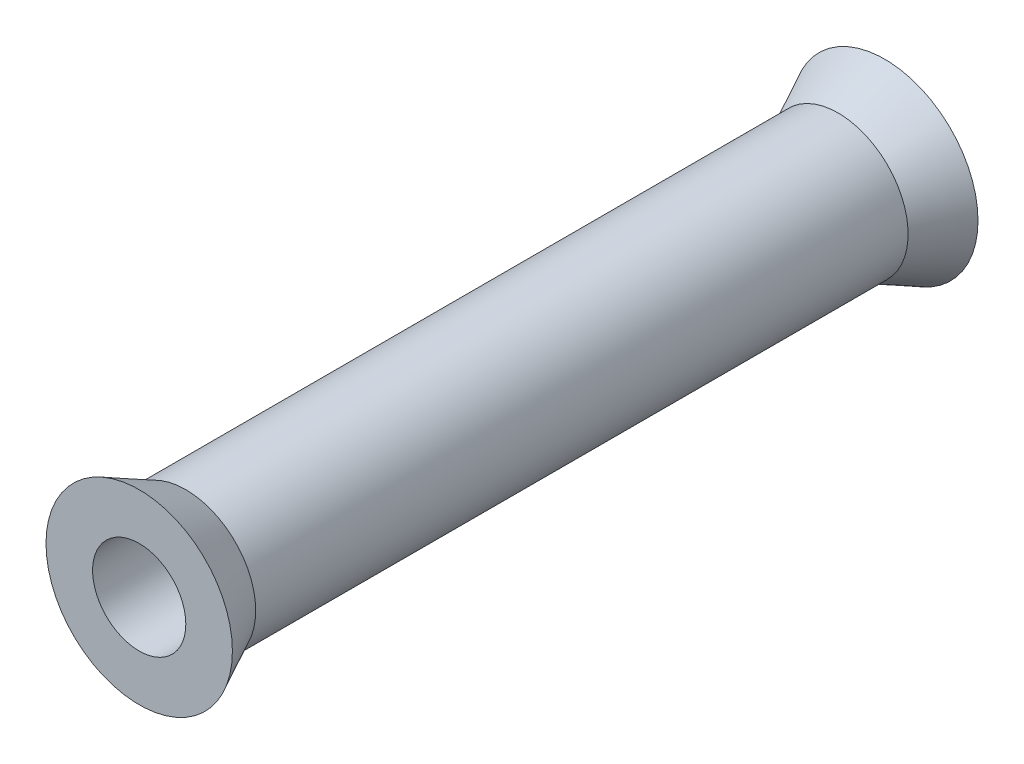
SolidWorks part; units mm, degrees
material "6061-T6 (SS)"
ref_plane "Front Plane" through (0, 0, 0) normal (0, 0, 1) x (1, 0, 0)
ref_plane "Top Plane" through (0, 0, 0) normal (0, 1, 0) x (1, 0, 0)
ref_plane "Right Plane" through (0, 0, 0) normal (1, 0, 0) x (0, 0, -1)
sketch "Sketch1" plane through (0, 0, 0) normal (0, 0, 1) x (1, 0, 0)
  circle A0 centre (0, 0) radius 6.35
  circle A1 centre (0, 0) radius 3.175
  dimension "D1" = 12.7
  dimension "D2" = 6.35
extrude "Boss-Extrude1" add sketch "Sketch1" along normal mid plane 50.8
sketch "Sketch2" plane through (0, 0, 0) normal (1, 0, 0) x (0, 0, -1)
  line L0 (0, 0) -> (0, 7.9375) construction
  line L1 (-28.575, 7.9375) -> (-22.225, 4.7625)
  line L2 (28.575, 11.1125) -> (-28.575, 11.1125)
  line L3 (28.575, 11.1125) -> (28.575, 4.7625)
  line L4 (28.575, 4.7625) -> (-28.575, 4.7625)
  line L5 (-28.575, 11.1125) -> (-28.575, 4.7625)
  line L6 (28.575, 11.1125) -> (-28.575, 4.7625) construction
  line L7 (28.575, 4.7625) -> (-28.575, 11.1125) construction
  line L8 (22.225, 4.7625) -> (28.575, 7.9375)
  line L9 (0, 0) -> (-13.5475, 0) construction
  dimension "D1" = 6.35
  dimension "D2" = 6.35
  dimension "D3" = 7.9375
  dimension "D4" = 6.35
  dimension "D5" = 57.15
revolve "Cut-Revolve2" cut sketch "Sketch2" angle 360 about L9
